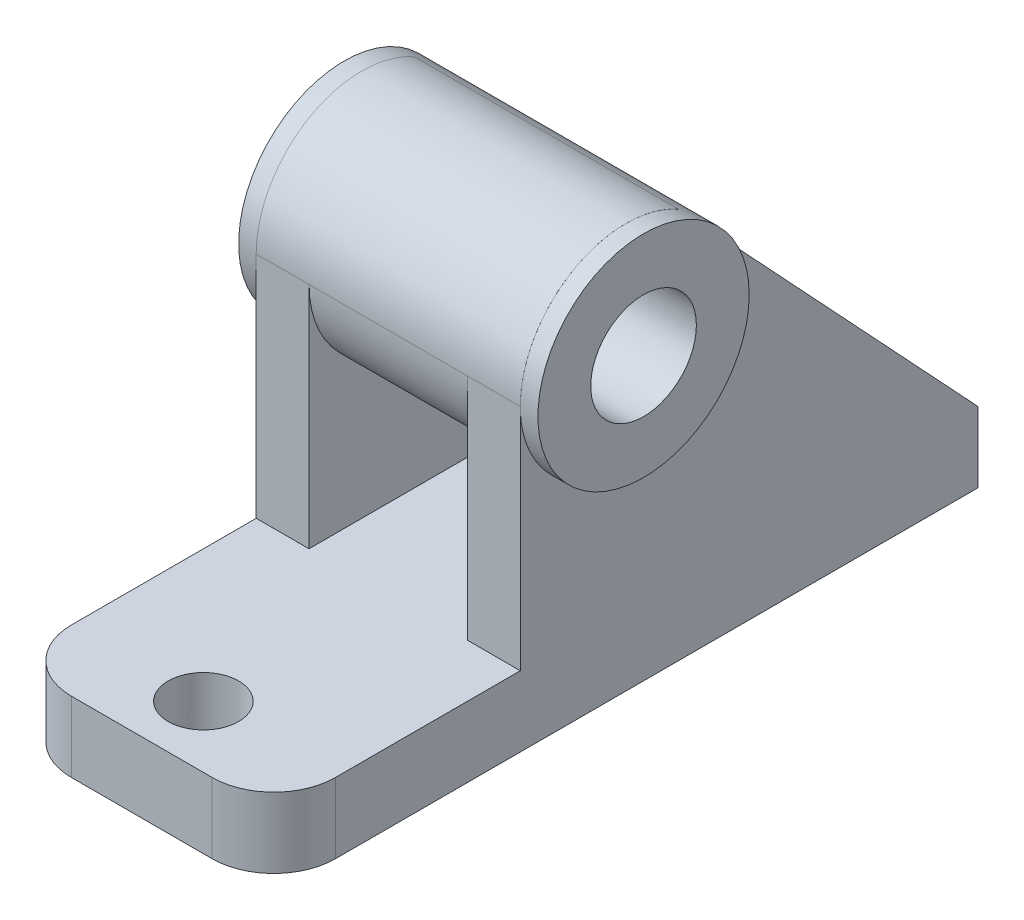
SolidWorks part; units mm, degrees
ref_plane "Front Plane" through (0, 0, 0) normal (0, 0, 1) x (1, 0, 0)
ref_plane "Top Plane" through (0, 0, 0) normal (0, 1, 0) x (1, 0, 0)
ref_plane "Right Plane" through (0, 0, 0) normal (1, 0, 0) x (0, 0, -1)
sketch "Sketch1" plane through (0, 0, 0) normal (1, 0, 0) x (0, 0, -1)
  line L0 (-45.9898, 2.4873) -> (34.0102, 2.4873)
  line L1 (34.0102, 2.4873) -> (34.0102, 10.4873)
  line L2 (34.0102, 10.4873) -> (-45.9898, 10.4873)
  line L3 (-45.9898, 10.4873) -> (-45.9898, 2.4873)
  dimension "D1" = 80
  dimension "D2" = 8
extrude "Boss-Extrude1" add sketch "Sketch1" against normal blind 30
fillet "Fillet1" radius 7 1 edges at (0, 6.4873, 45.9898)
fillet "Fillet2" radius 7 1 edges at (-30, 6.4873, 45.9898)
sketch "Sketch2" plane through (0, 0, 0) normal (1, 0, 0) x (0, 0, -1)
  line L0 (-17.9898, 10.4873) -> (-17.9898, 36.4873)
  line L1 (34.0102, 10.4873) -> (-38.9898, 10.4873) construction
  line L2 (-17.9898, 10.4873) -> (34.0102, 10.4873)
  line L3 (34.0102, 10.4873) -> (0, 46.8928)
  line L4 (-38.9898, 10.4873) -> (-38.9898, 2.4873) construction
  arc A0 (-17.9898, 36.4873) -> (0, 46.8928) centre (-5.9856, 36.4873) cw
  dimension "D1" = 21
  dimension "D2" = 26
extrude "Boss-Extrude3" add sketch "Sketch2" against normal blind 30
sketch "Sketch4" plane through (0, 0, 17.9898) normal (0, 0, 1) x (1, 0, 0)
  line L0 (-24, 10.4873) -> (-24, 36.4873)
  line L1 (-30, 10.4873) -> (0, 10.4873) construction
  line L2 (-30, 36.4873) -> (0, 36.4873) construction
  line L3 (-24, 36.4873) -> (-6, 36.4873)
  line L4 (-6, 36.4873) -> (-6, 10.4873)
  line L5 (-6, 10.4873) -> (-24, 10.4873)
  line L6 (-30, 36.4873) -> (-30, 10.4873) construction
  line L7 (0, 36.4873) -> (0, 10.4873) construction
  dimension "D1" = 6
  dimension "D2" = 6
extrude "Cut-Extrude1" cut sketch "Sketch4" against normal blind 26
sketch "Sketch5" plane through (0, 0, 0) normal (1, 0, 0) x (0, 0, -1)
  circle A0 centre (-5.9856, 36.4873) radius 12
  dimension "D1" = 24
extrude "Boss-Extrude4" add sketch "Sketch5" against normal blind 32
sketch "Sketch6" plane through (0, 0, 0) normal (1, 0, 0) x (0, 0, -1)
  circle A0 centre (-5.9856, 36.4873) radius 12
extrude "Boss-Extrude5" add sketch "Sketch6" along normal blind 2
sketch "Sketch7" plane through (2, 0, 0) normal (1, 0, 0) x (0, 0, -1)
  circle A0 centre (-5.9856, 36.4873) radius 6
  dimension "D1" = 12
extrude "Cut-Extrude2" cut sketch "Sketch7" against normal up to next
sketch "Sketch8" plane through (0, 10.4873, 0) normal (0, 1, 0) x (1, 0, 0)
  line L0 (-19, -38.9898) -> (-11, -38.9898) construction
  line L1 (-23, -45.9898) -> (-7, -45.9898) construction
  circle A0 centre (-15, -38.9898) radius 4
  dimension "D1" = 8
  dimension "D2" = 7
extrude "Cut-Extrude3" cut sketch "Sketch8" against normal up to next
